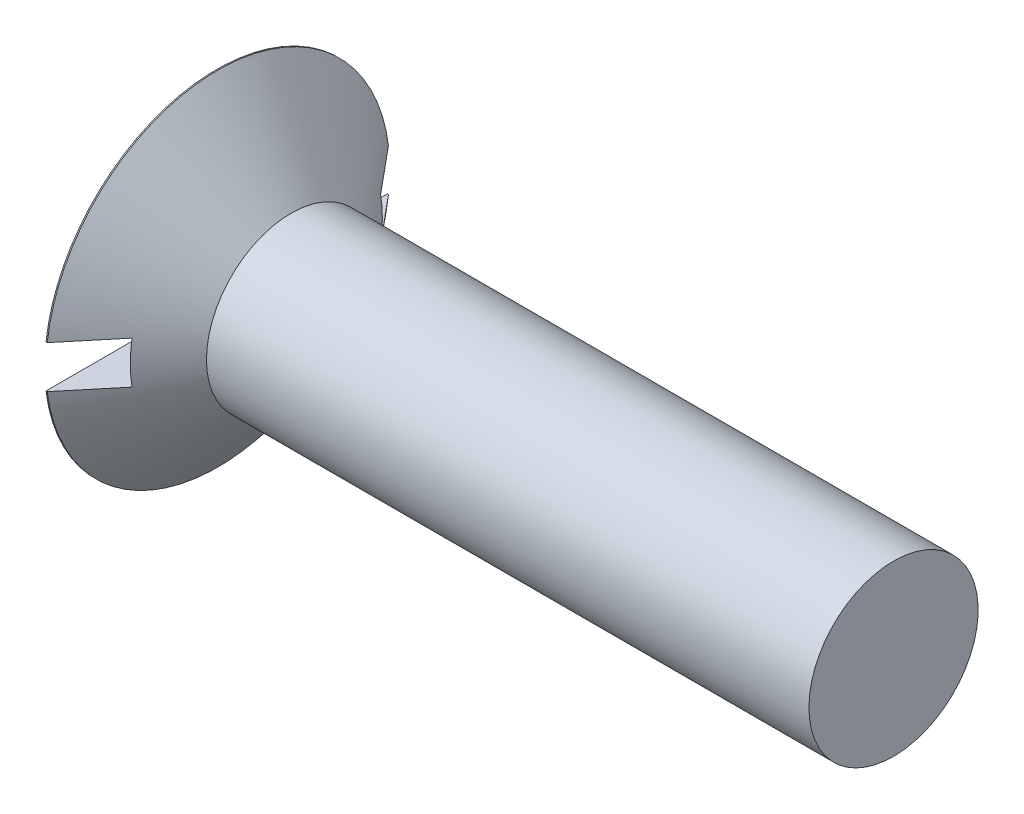
SolidWorks part; units mm, degrees
revolve "Base-Revolve" add sketch "BodySke" angle 360 about L5
sketch "BodySke" plane through (0, 0, 0) normal (0, 0, 1) x (1, 0, 0)
  line L0 (0, 0) -> (0, 9.6774)
  line L1 (0, 9.6774) -> (0.0669, 9.6774)
  line L2 (4.191, 4.7625) -> (38.1, 4.7625)
  line L3 (38.1, 4.7625) -> (38.1, 0)
  line L4 (38.1, 0) -> (0, 0)
  line L5 (-6.35, 0) -> (82.55, 0) construction
  line L6 (4.191, -4.7625) -> (38.1, -4.7625) construction
  line L7 (0.0669, -9.6774) -> (4.191, -4.7625) construction
  line L8 (0.0669, 9.6774) -> (4.191, 4.7625)
  line L9 (0, -9.6774) -> (0.0669, -9.6774) construction
  line L10 (5.7785, 6.35) -> (5.7785, -3.175) construction
  line L11 (6.35, 6.35) -> (6.35, -3.175) construction
  dimension "Diameter" = 9.525
  dimension "Length" = 38.1
  dimension "Head_ht" = 4.191
  dimension "Head_dia" = 19.3548
  dimension "Head_ang" = 100
  dimension "D6" = 0.0669
  dimension "Advance" = 1.5875
  dimension "Thread_nom" = 31.75
cosmetic thread "ThreadCosmetic" [suppressed] parameters "Thread_length"=31.75, "Thread_minor"=7.9248
extrude "Slot" cut sketch "Sketch2" against normal blind 2.2352
sketch "Sketch2" plane through (0, 0, 0) normal (-1, 0, 0) x (0, 0, 1)
  line L0 (-9.6774, -1.1938) -> (9.6774, -1.1938)
  line L1 (-9.6774, -1.1938) -> (-9.6774, 1.1938)
  line L2 (9.6774, 1.1938) -> (-9.6774, 1.1938)
  line L3 (9.6774, 1.1938) -> (9.6774, -1.1938)
  dimension "Slot_width" = 2.3876
  dimension "D1" = 1.1938
  dimension "D2" = 19.3548
  dimension "D3" = 9.6774
ref_plane "Plane1" through (0, 0, 0) normal (0, 0, 1) x (1, 0, 0)
ref_plane "Plane2" through (0, 0, 0) normal (0, 1, 0) x (1, 0, 0)
ref_plane "Plane3" through (0, 0, 0) normal (1, 0, 0) x (0, 0, -1)
sketch "Sketch3" plane through (0, 0, 0) normal (-1, 0, 0) x (0, 0, 1)
  line L0 (-1.0922, 6.6421) -> (1.0922, 6.6421)
  line L1 (1.0922, 6.6421) -> (1.0922, -6.6421)
  line L2 (1.0922, -6.6421) -> (-1.0922, -6.6421)
  line L3 (-1.0922, -6.6421) -> (-1.0922, 6.6421)
  dimension "Cross_dia" = 13.2842
  dimension "Cross_width" = 2.1844
  dimension "D1" = 6.6421
  dimension "D2" = 1.0922
ref_plane "Plane4" through (7.9756, 0, 0) normal (-1, 0, 0) x (0, 0, 1)
sketch "Sketch4" plane through (7.9756, 0, 0) normal (-1, 0, 0) x (0, 0, 1)
  line L0 (-0.5461, 0.5461) -> (0.5461, 0.5461)
  line L3 (0.5461, 0.5461) -> (0.5461, -0.5461)
  line L4 (0.5461, -0.5461) -> (-0.5461, -0.5461)
  line L5 (-0.5461, -0.5461) -> (-0.5461, 0.5461)
  dimension "D2" = 1.0922
  dimension "D1" = 1.0922
  dimension "D3" = 0.5461
  dimension "D4" = 0.5461
loft "Cross" cut profiles "Sketch3", "Sketch4"
pattern_circular "CirPattern1" count 2 every 90 about axis through (0, 0, 0) along (1, 0, 0) of "Cross"
sketch "ThdSchSke" plane through (0, 0, 0) normal (0, 0, 1) x (1, 0, 0)
  line L0 (6.35, -3.9624) -> (5.7898, -4.7625)
  line L1 (6.35, -3.9624) -> (6.9103, -4.7625)
  line L2 (6.9103, -4.7625) -> (6.9103, -5.9531)
  line L3 (-3.175, 0) -> (5.1513, 0) construction
  line L5 (6.9103, -5.9531) -> (5.7898, -5.9531)
  line L6 (5.7898, -5.9531) -> (5.7898, -4.7625)
  line L7 (0, 9.6774) -> (0, 1.1938) construction
  dimension "Diameter" = 9.525
  dimension "Thread_minor" = 7.9248
  dimension "Start" = 6.35
revolve "ThreadSchematic" [suppressed] cut sketch "ThdSchSke" angle 360 about L3
pattern_linear "ThdSchPat" [suppressed]
equation "\"D1@Sketch3\" = \"Cross_dia@Sketch3\" / 2"
equation "\"D2@Sketch3\" = \"Cross_width@Sketch3\" / 2"
equation "\"D1@Sketch4\" = \"Cross_width@Sketch3\" *.5"
equation "\"D2@Sketch4\" = \"D1@Sketch4\""
equation "\"D4@Sketch4\" = \"D2@Sketch4\" / 2"
equation "\"D3@Sketch4\" = \"D1@Sketch4\" / 2"
equation "\"D1@Sketch2\" = \"Slot_width@Sketch2\" / 2"
equation "\"D2@Sketch2\" = \"Head_dia@BodySke\""
equation "\"D3@Sketch2\" = \"D2@Sketch2\" / 2"
equation "\"Thread_length@ThreadCosmetic\" = ((sgn( (\"Length@BodySke\" - \"Advance@BodySke\" - \"Head_ht@BodySke\" ) - \"Thread_nom@BodySke\" )-1)*( (\"Length@BodySke\" - \"Advance@BodySke\" - \"Head_ht@BodySke\" ) - \"Thread_nom@BodySke\" ))/-2+ \"Thread_nom@BodySke\""
equation "\"Thread_minor@ThdSchSke\" = \"Thread_minor@ThreadCosmetic\""
equation "\"Diameter@ThdSchSke\" = \"Diameter@BodySke\""
equation "\"Overcut@ThdSchSke\" = \"Diameter@BodySke\" * 1.25"
equation "\"Start@ThdSchSke\" = 0.000001 + \"Length@BodySke\" - \"Thread_length@ThreadCosmetic\"  '---Countersunk---"
equation "\"Num_threads@ThdSchPat\" = int( \"Thread_length@ThreadCosmetic\" / \"Advance@BodySke\" + 0.999 )  + 1"
equation "\"Advance@ThdSchPat\" = \"Thread_length@ThreadCosmetic\" /  (\"Num_threads@ThdSchPat\" - 1) 'relax it"
